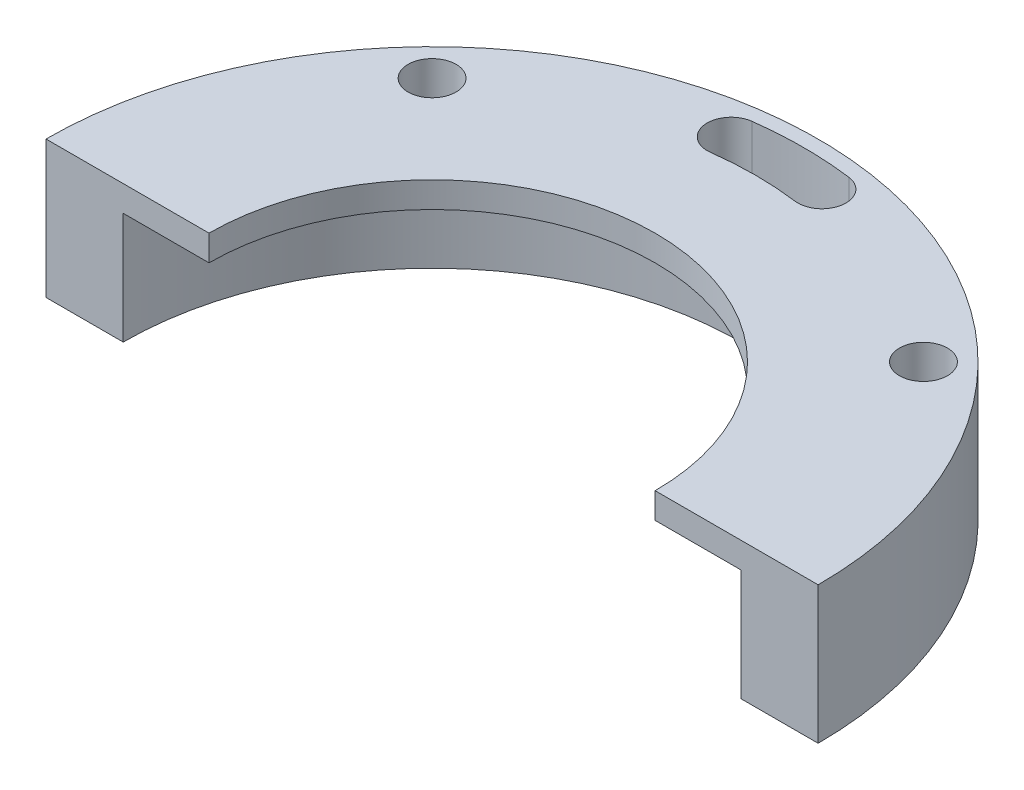
SolidWorks part; units mm, degrees
material "6061-T6 (SS)"
ref_plane "Front Plane" through (0, 0, 0) normal (0, 0, 1) x (1, 0, 0)
ref_plane "Top Plane" through (0, 0, 0) normal (0, 1, 0) x (1, 0, 0)
ref_plane "Right Plane" through (0, 0, 0) normal (1, 0, 0) x (0, 0, -1)
sketch "Sketch1" plane through (0, 0, 0) normal (0, 1, 0) x (1, 0, 0)
  circle A0 centre (0, 0) radius 28.575
  dimension "D1" = 57.15
extrude "Boss-Extrude1" add sketch "Sketch1" along normal blind 10.16 contours A0
sketch "Sketch2" plane through (0, 0, 0) normal (0, -1, 0) x (1, 0, 0)
  circle A0 centre (0, 0) radius 16.51
  dimension "D1" = 33.02
extrude "Cut-Extrude1" cut sketch "Sketch2" against normal through all
sketch "Sketch3" plane through (0, 0, 0) normal (0, -1, 0) x (1, 0, 0)
  circle A0 centre (0, 0) radius 22.86
  dimension "D1" = 45.72
extrude "Cut-Extrude2" cut sketch "Sketch3" against normal blind 8.255
sketch "Sketch4" plane through (0, 10.16, 0) normal (0, 1, 0) x (1, 0, 0)
  line L1 (-39.5745, 0) -> (49.3406, 0)
  line L2 (-39.5745, 0) -> (-39.5745, -51.3525)
  line L3 (-39.5745, -51.3525) -> (49.3406, -51.3525)
  line L4 (49.3406, 0) -> (49.3406, -51.3525)
extrude "Cut-Extrude3" cut sketch "Sketch4" against normal through all
sketch "Sketch6" plane through (0, 0, 0) normal (0, -1, 0) x (1, 0, 0)
  line L0 (0, 0) -> (0, -44.8534) construction
  line L1 (0, 0) -> (18.185, -18.185) construction
  line L2 (0, 0) -> (-18.185, -18.185) construction
  circle A0 centre (0, 0) radius 25.7175 construction
  circle A1 centre (18.185, -18.185) radius 1.778
  circle A2 centre (-18.185, -18.185) radius 1.778
  dimension "D1" = 51.435
  dimension "D4" = 3.556
  dimension "D5" = 3.556
  dimension "D2" = 45
  dimension "D3" = 45
extrude "Cut-Extrude4" cut sketch "Sketch6" against normal up to next
sketch "Sketch7" plane through (0, 10.16, 0) normal (0, 1, 0) x (1, 0, 0)
  line L0 (0, 0) -> (0, 25.7175) construction
  line L1 (0, 0) -> (3.3568, 25.4975) construction
  line L2 (0, 0) -> (-3.3568, 25.4975) construction
  circle A0 centre (0, 0) radius 25.7175 construction
  arc A1 (3.1247, 23.7347) -> (-3.1247, 23.7347) centre (0, 0) ccw
  arc A2 (3.5889, 27.2603) -> (-3.5889, 27.2603) centre (0, 0) ccw
  arc A3 (3.1247, 23.7347) -> (3.5889, 27.2603) centre (3.3568, 25.4975) ccw
  arc A4 (-3.5889, 27.2603) -> (-3.1247, 23.7347) centre (-3.3568, 25.4975) ccw
  dimension "D1" = 15
  dimension "D2" = 7.5
extrude "Cut-Extrude5" cut sketch "Sketch7" against normal through all
equation "\"D5@Sketch6\"=\"D4@Sketch6\""
equation "\"D2@Sketch7\"=\"D1@Sketch7\"/2"
